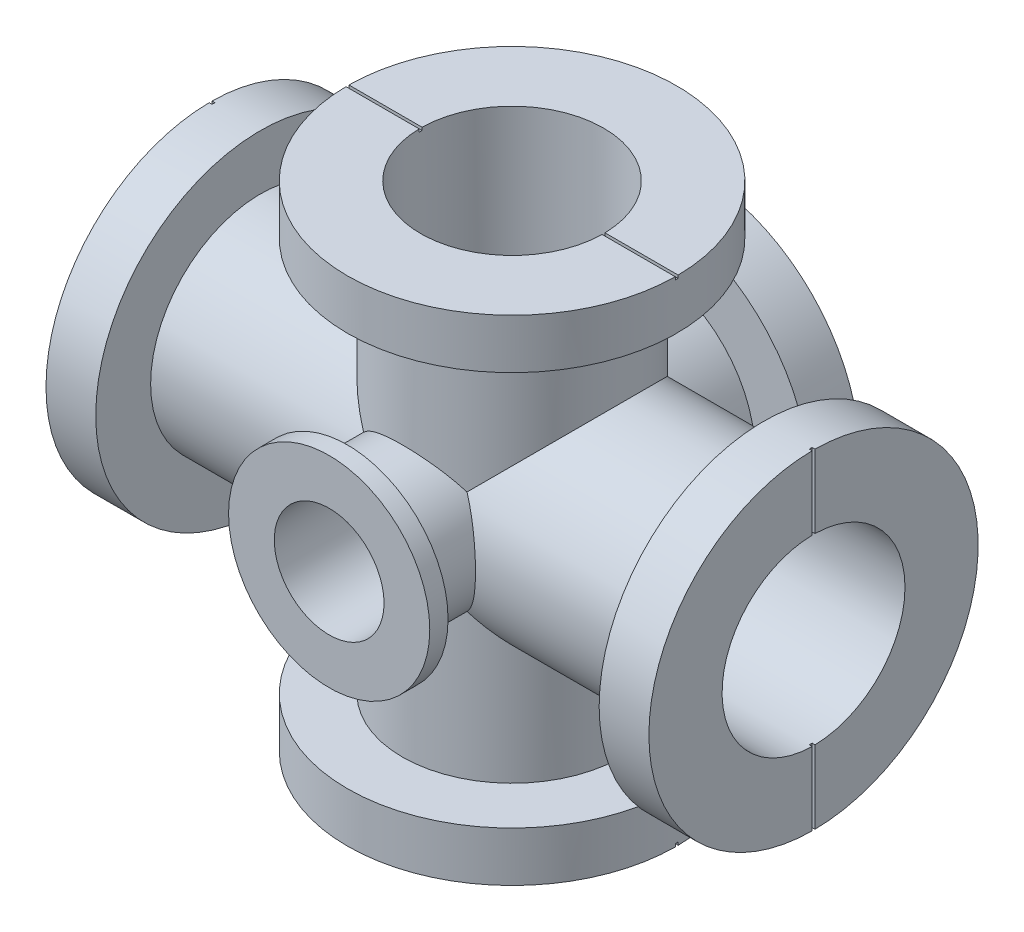
SolidWorks part; units mm, degrees
ref_plane "Front Plane" through (0, 0, 0) normal (0, 0, 1) x (1, 0, 0)
ref_plane "Top Plane" through (0, 0, 0) normal (0, 1, 0) x (1, 0, 0)
ref_plane "Right Plane" through (0, 0, 0) normal (1, 0, 0) x (0, 0, -1)
sketch "Sketch1" plane through (0, 0, 0) normal (1, 0, 0) x (0, 0, -1)
  line L0 (0, 50.2038) -> (0, -62.5435) construction
  line L1 (0, 0) -> (-80.9062, 0) construction
  line L2 (-80.9062, 0) -> (88.6117, 0) construction
  line L3 (-63.5, 19.05) -> (-63.5, 34.925)
  line L4 (-63.5, 34.925) -> (-57.15, 34.925)
  line L5 (-57.15, 34.925) -> (-57.15, 25.4)
  line L6 (-57.15, 25.4) -> (0, 25.4)
  line L7 (0, 25.4) -> (0, 19.05)
  line L8 (0, 19.05) -> (-63.5, 19.05)
  line L9 (0, 38.1) -> (46.228, 38.1)
  line L10 (46.228, 38.1) -> (46.228, 57.15)
  line L11 (46.228, 57.15) -> (63.5, 57.15)
  line L12 (63.5, 57.15) -> (63.5, 31.75)
  line L13 (63.5, 31.75) -> (0, 31.75)
  line L14 (0, 31.75) -> (0, 38.1)
  dimension "D1" = 6.35
  dimension "D2" = 63.5
  dimension "D3" = 114.3
  dimension "D4" = 17.272
  dimension "D5" = 63.5
  dimension "D6" = 6.35
  dimension "D7" = 6.35
  dimension "D8" = 38.1
  dimension "D9" = 69.85
  dimension "D10" = 63.5
revolve "Revolve2" add sketch "Sketch1" angle 360 about L2
sketch "Sketch2" plane through (0, 0, 0) normal (0, 1, 0) x (1, 0, 0)
  line L0 (0, 34.0784) -> (0, -49.4321) construction
  line L1 (-75.638, 0) -> (86.9065, 0) construction
  line L2 (-104.648, 31.75) -> (-104.648, 57.15)
  line L3 (-104.648, 57.15) -> (-87.376, 57.15)
  line L4 (-87.376, 57.15) -> (-87.376, 38.1)
  line L5 (-87.376, 38.1) -> (87.376, 38.1)
  line L6 (-104.648, 31.75) -> (104.648, 31.75)
  line L7 (87.376, 57.15) -> (87.376, 38.1)
  line L8 (104.648, 57.15) -> (87.376, 57.15)
  line L9 (104.648, 31.75) -> (104.648, 57.15)
  point P12 (0, 31.75)
  point P13 (0, 38.1)
  dimension "D1" = 63.5
  dimension "D2" = 114.3
  dimension "D3" = 209.296
  dimension "D4" = 17.272
  dimension "D5" = 6.35
revolve "Revolve3" add sketch "Sketch2" angle 360 about L1
sketch "Sketch3" plane through (0, 0, 0) normal (0, 0, 1) x (1, 0, 0)
  line L0 (0, 84.837) -> (0, -87.436) construction
  line L1 (-74.2556, 0) -> (79.2679, 0) construction
  line L2 (-38.1, -68.453) -> (-38.1, 68.453)
  line L3 (-38.1, 68.453) -> (-57.15, 68.453)
  line L4 (-57.15, 68.453) -> (-57.15, 85.725)
  line L5 (-57.15, 85.725) -> (-31.75, 85.725)
  line L6 (-31.75, 85.725) -> (-31.75, -85.725)
  line L7 (-57.15, -85.725) -> (-31.75, -85.725)
  line L8 (-57.15, -68.453) -> (-57.15, -85.725)
  line L9 (-38.1, -68.453) -> (-57.15, -68.453)
  point P12 (-31.75, 0)
  point P15 (-38.1, 0)
  dimension "D1" = 63.5
  dimension "D2" = 114.3
  dimension "D3" = 171.45
  dimension "D4" = 6.35
  dimension "D5" = 17.272
revolve "Revolve4" add sketch "Sketch3" angle 360 about L0
sketch "Sketch5" plane through (0, 0, 63.5) normal (0, 0, 1) x (1, 0, 0)
  circle A0 centre (0, 0) radius 19.05
extrude "Cut-Extrude1" cut sketch "Sketch5" against normal blind 63.5
sketch "Sketch6" plane through (0, 0, -63.5) normal (0, 0, -1) x (-1, 0, 0)
  circle A0 centre (0, 0) radius 31.75
extrude "Cut-Extrude2" cut sketch "Sketch6" against normal blind 63.5
sketch "Sketch7" plane through (-104.648, 0, 0) normal (-1, 0, 0) x (0, 0, 1)
  circle A0 centre (0, 0) radius 31.75
extrude "Cut-Extrude3" cut sketch "Sketch7" against normal through all
sketch "Sketch8" plane through (0, 85.725, 0) normal (0, 1, 0) x (-1, 0, 0)
  circle A0 centre (0, 0) radius 31.75
extrude "Cut-Extrude4" cut sketch "Sketch8" against normal through all
sketch "Sketch9" plane through (0, 85.725, 0) normal (0, 1, 0) x (-1, 0, 0)
  line L0 (0, -76.0842) -> (0, 90.434) construction
  line L1 (-0.5, -63.5) -> (0.5, -63.5)
  line L2 (-57.15, -63.5) -> (57.15, -63.5) construction
  line L3 (-31.75, -63.5) -> (31.75, -63.5) construction
  line L4 (0.5, -63.5) -> (0.5, -62.5)
  line L5 (0.5, -62.5) -> (-0.5, -62.5)
  line L6 (118.2521, 0) -> (-121.0367, 0) construction
  line L7 (-0.5, -63.5) -> (-0.5, -62.5)
  line L8 (104.648, 0.5) -> (104.648, -0.5)
  line L9 (104.648, -57.15) -> (104.648, 57.15) construction
  line L10 (104.648, -0.5) -> (103.648, -0.5)
  line L11 (103.648, -0.5) -> (103.648, 0.5)
  line L12 (104.648, 0.5) -> (103.648, 0.5)
  line L13 (-104.648, 0.5) -> (-103.648, 0.5)
  line L14 (-103.648, -0.5) -> (-103.648, 0.5)
  line L15 (-104.648, -0.5) -> (-103.648, -0.5)
  line L16 (-104.648, 0.5) -> (-104.648, -0.5)
  point P3 (-104.648, 0)
  point P14 (0, -62.5)
  point P15 (0, -63.5)
  point P22 (103.648, 0)
  point P23 (104.648, 0)
  point P24 (-103.648, 0)
  dimension "D1" = 1
  dimension "D2" = 1
  dimension "D3" = 1
  dimension "D4" = 1
extrude "Cut-Extrude5" cut sketch "Sketch9" against normal through all
sketch "Sketch10" plane through (-104.648, 0, 0) normal (-1, 0, 0) x (0, 0, 1)
  line L0 (-93.0838, 0) -> (118.6704, 0) construction
  line L1 (0, 93.8724) -> (0, -92.4948) construction
  line L2 (0.5, 85.725) -> (-0.5, 85.725)
  line L3 (57.15, 85.725) -> (-57.15, 85.725) construction
  line L4 (-0.5, 85.725) -> (-0.5, 84.725)
  line L5 (-0.5, 84.725) -> (0.5, 84.725)
  line L6 (0.5, 85.725) -> (0.5, 84.725)
  line L7 (0.5, -85.725) -> (0.5, -84.725)
  line L8 (-0.5, -84.725) -> (0.5, -84.725)
  line L9 (-0.5, -85.725) -> (-0.5, -84.725)
  line L10 (0.5, -85.725) -> (-0.5, -85.725)
  point P5 (0, -85.725)
  point P12 (0, 84.725)
  point P13 (0, 85.725)
  point P14 (0, -84.725)
  dimension "D1" = 1
  dimension "D2" = 1
extrude "Cut-Extrude6" cut sketch "Sketch10" against normal through all
